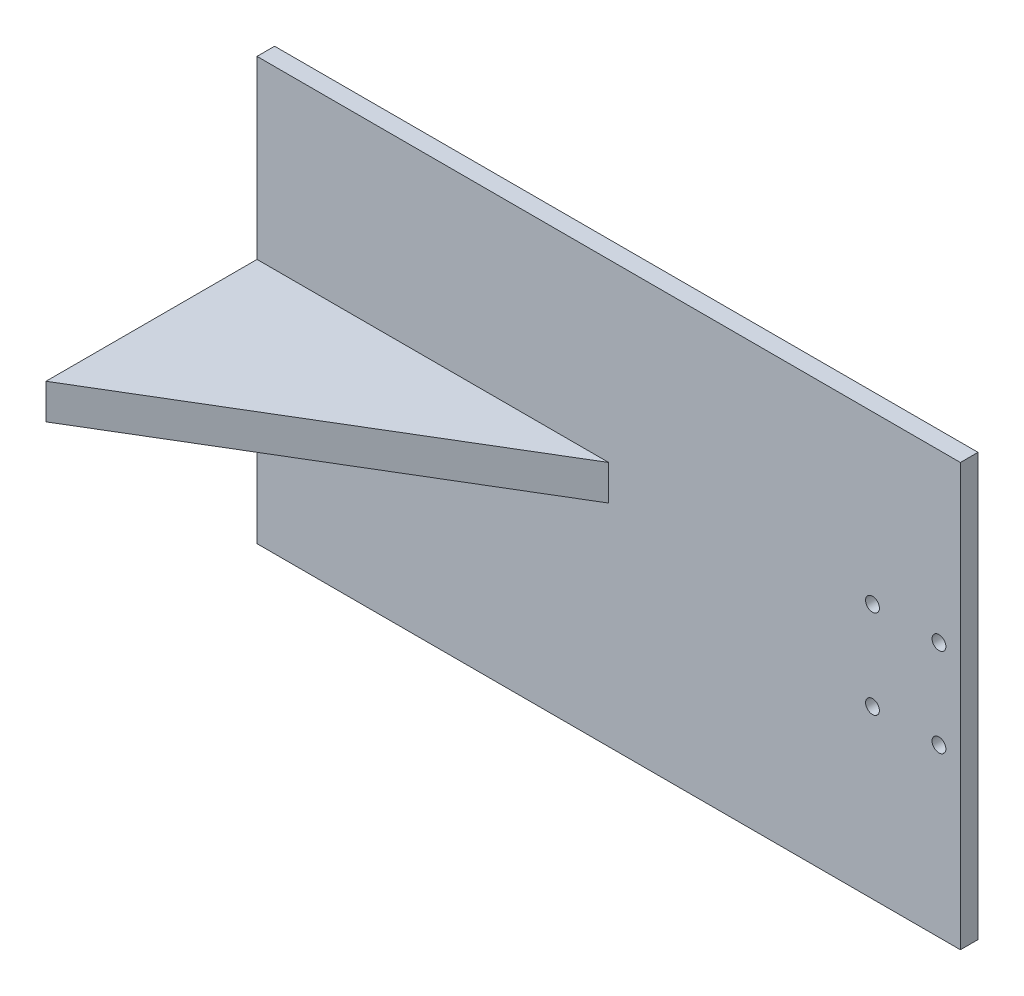
SolidWorks part; units mm, degrees
ref_plane "Plan de face" through (0, 0, 0) normal (0, 0, 1) x (1, 0, 0)
ref_plane "Plan de dessus" through (0, 0, 0) normal (0, 1, 0) x (1, 0, 0)
ref_plane "Plan de droite" through (0, 0, 0) normal (1, 0, 0) x (0, 0, -1)
sketch "Esquisse1" plane through (0, 0, 0) normal (0, 0, 1) x (1, 0, 0)
  line L1 (-63.5, 38.1) -> (63.5, 38.1)
  line L2 (-63.5, 38.1) -> (-63.5, -38.1)
  line L3 (-63.5, -38.1) -> (63.5, -38.1)
  line L4 (63.5, 38.1) -> (63.5, -38.1)
  point P4 (0, 38.1)
  point P6 (63.5, 0)
  point P7 (-63.5, 0)
  dimension "D1" = 127
  dimension "D2" = 76.2
extrude "Boss.-Extru.1" add sketch "Esquisse1" along normal mid plane 3.175
sketch "Esquisse2" plane through (0, 0, 1.5875) normal (0, 0, 1) x (1, 0, 0)
  line L1 (-63.5, 38.1) -> (-63.5, -38.1) construction
  circle A0 centre (47.625, 8) radius 1.2497
  circle A1 centre (59.625, 8) radius 1.2497
  dimension "D1" = 12
  dimension "D2" = 8
  dimension "D3" = 2.4994
  dimension "D4" = 111.125
extrude "Enlèv. mat.-Extru.1" cut sketch "Esquisse2" against normal through all
mirror "Symétrie1" about plane through (0, 0, 0) normal (0, 1, 0) of "Enlèv. mat.-Extru.1"
sketch "Sketch1" plane through (0, 0, 0) normal (0, 1, 0) x (1, 0, 0)
  line L0 (-63.5, -1.5875) -> (-63.5, -39.6875)
  line L1 (-63.5, -39.6875) -> (0, -1.5875)
  line L2 (63.5, -1.5875) -> (-63.5, -1.5875) construction
  line L3 (0, -1.5875) -> (-63.5, -1.5875)
  dimension "D1" = 38.1
  dimension "D2" = 63.5
extrude "Boss-Extrude1" add sketch "Sketch1" along normal blind 6.35
